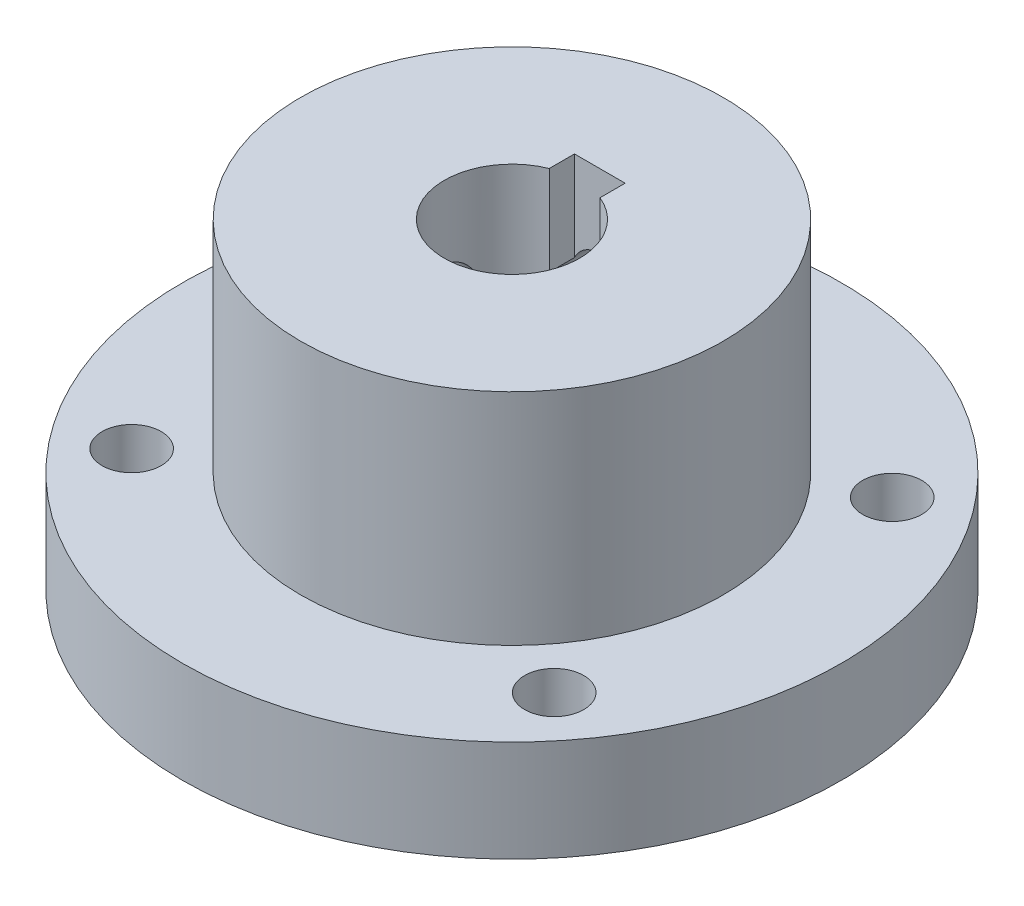
SolidWorks part; units mm, degrees
ref_plane "Front Plane" through (0, 0, 0) normal (0, 0, 1) x (1, 0, 0)
ref_plane "Top Plane" through (0, 0, 0) normal (0, 1, 0) x (1, 0, 0)
ref_plane "Right Plane" through (0, 0, 0) normal (1, 0, 0) x (0, 0, -1)
sketch "Sketch1" plane through (0, 0, 0) normal (0, 1, 0) x (1, 0, 0)
  line L1 (-14.0712, 13.5) -> (14.0712, 13.5)
  line L3 (-14.0712, -13.5) -> (14.0712, -13.5)
  line L5 (-12.5, 10) -> (12.5, 10) construction
  line L6 (-12.5, 10) -> (-12.5, -10) construction
  line L7 (-12.5, -10) -> (12.5, -10) construction
  line L8 (12.5, 10) -> (12.5, -10) construction
  line L9 (-12.5, 10) -> (12.5, -10) construction
  line L10 (-12.5, -10) -> (12.5, 10) construction
  arc A0 (-14.0712, 13.5) -> (-14.0712, -13.5) centre (0, 0) ccw
  circle A1 centre (0, 0) radius 4
  arc A2 (14.0712, -13.5) -> (14.0712, 13.5) centre (0, 0) ccw
  circle A3 centre (-12.5, 10) radius 1.75
  circle A4 centre (-12.5, -10) radius 1.75
  circle A5 centre (12.5, -10) radius 1.75
  circle A6 centre (12.5, 10) radius 1.75
  dimension "D1" = 39
  dimension "D2" = 8
  dimension "D7" = 3.5
  dimension "D3" = 13.5
  dimension "D4" = 13.5
  dimension "D5" = 25
  dimension "D6" = 20
extrude "Boss-Extrude1" add sketch "Sketch1" along normal blind 6
sketch "Sketch2" plane through (0, 6, 0) normal (0, 1, 0) x (1, 0, 0)
  circle A0 centre (0, 0) radius 12.5
  circle A1 centre (0, 0) radius 4 construction
  circle A2 centre (0, 0) radius 4
  dimension "D1" = 25
extrude "Boss-Extrude2" add sketch "Sketch2" along normal blind 13
sketch "Sketch4" plane through (0, 19, 0) normal (0, 1, 0) x (1, 0, 0)
  line L0 (0, 0) -> (0, 10.571) construction
  line L1 (0, 4) -> (3.0028, 4) construction
  line L2 (0, 0) -> (0, -4) construction
  line L3 (-1.5, 5.2) -> (1.5, 5.2)
  line L4 (-1.5, 5.2) -> (-1.5, 2.8)
  line L5 (-1.5, 2.8) -> (1.5, 2.8)
  line L6 (1.5, 5.2) -> (1.5, 2.8)
  line L7 (-1.5, 5.2) -> (1.5, 2.8) construction
  line L8 (-1.5, 2.8) -> (1.5, 5.2) construction
  circle A0 centre (0, 0) radius 4 construction
  point P11 (0, -4)
  dimension "D1" = 3
  dimension "D2" = 9.2
extrude "Cut-Extrude2" cut sketch "Sketch4" against normal blind 30
sketch "Sketch3" plane through (0, 0, -13.5) normal (0, 0, -1) x (-1, 0, 0)
  line L0 (12.5, 19) -> (-12.5, 19) construction
  line L1 (12.5, 19) -> (-12.5, 19) construction
  line L2 (0, 19) -> (0, 13) construction
  line L3 (0, 13) -> (7.5, 13) construction
  line L4 (0, 13) -> (-7.5, 13) construction
  circle A0 centre (-7.5, 13) radius 2
  circle A1 centre (7.5, 13) radius 2
  circle A2 centre (0, 13) radius 1.65
  dimension "D4" = 4
  dimension "D5" = 3.3
  dimension "D1" = 6
  dimension "D2" = 7.5
  dimension "D3" = 7.5
extrude "Cut-Extrude3" cut sketch "Sketch3" against normal blind 14 contours A2
sketch "Sketch5" plane through (0, 0, 0) normal (1, 0, 0) x (0, 0, -1)
  line L0 (12.5, 19) -> (-12.5, 19) construction
  line L1 (12.5, 19) -> (-12.5, 19) construction
  line L2 (0, 19) -> (0, 13) construction
  circle A0 centre (0, 13) radius 1.65
  dimension "D2" = 3.3
  dimension "D1" = 6
extrude "Cut-Extrude4" cut sketch "Sketch5" against normal blind 30
sketch "Sketch6" plane through (0, 6, 0) normal (0, 1, 0) x (1, 0, 0)
  line L2 (14.0712, 13.5) -> (-14.0712, 13.5)
  line L3 (-14.0712, -13.5) -> (14.0712, -13.5)
  line L4 (14.0712, 13.5) -> (-14.0712, 13.5)
  line L5 (-14.0712, -13.5) -> (14.0712, -13.5)
  circle A0 centre (0, 0) radius 19.5
  arc A2 (14.0712, -13.5) -> (14.0712, 13.5) centre (0, 0) ccw
  arc A3 (-14.0712, 13.5) -> (-14.0712, -13.5) centre (0, 0) ccw
  arc A4 (14.0712, -13.5) -> (14.0712, 13.5) centre (0, 0) ccw
  arc A5 (-14.0712, 13.5) -> (-14.0712, -13.5) centre (0, 0) ccw
  line M9 (14.0712, 13.5) -> (-14.0712, 13.5)
  line M11 (-14.0712, -13.5) -> (14.0712, -13.5)
  dimension "D1" = 0
extrude "Boss-Extrude3" add sketch "Sketch6" against normal up to surface (6 mm away) contours A0 M9 | A0 M11 up to face at (0, 0, -2.527)
